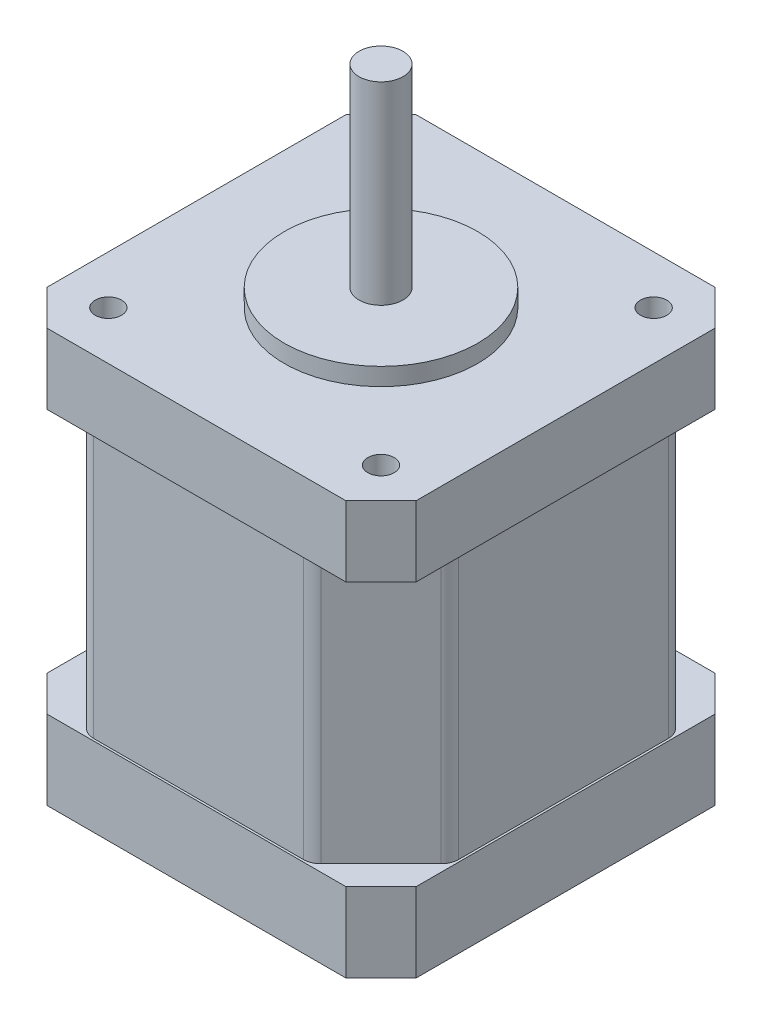
SolidWorks part; units mm, degrees
material "Commercially Pure CP-Ti UNS R50700  Grade 4 (SS)"
ref_plane "Front Plane" through (0, 0, 0) normal (0, 0, 1) x (1, 0, 0)
ref_plane "Top Plane" through (0, 0, 0) normal (0, 1, 0) x (1, 0, 0)
ref_plane "Right Plane" through (0, 0, 0) normal (1, 0, 0) x (0, 0, -1)
sketch "Sketch1" plane through (0, 0, 0) normal (0, 1, 0) x (1, 0, 0)
  line L0 (-21, 21) -> (21, -21) construction
  line L1 (-17, 21) -> (17, 21)
  line L2 (-21, 17) -> (-21, -17)
  line L3 (-17, -21) -> (17, -21)
  line L4 (21, 17) -> (21, -17)
  line L5 (-21, 17) -> (-17, 21)
  line L6 (-21, -17) -> (-17, -21)
  line L7 (17, -21) -> (21, -17)
  line L8 (17, 21) -> (21, 17)
  line L9 (-15.5, 15.5) -> (15.5, 15.5) construction
  line L10 (15.5, 15.5) -> (15.5, -15.5) construction
  line L11 (15.5, -15.5) -> (-15.5, -15.5) construction
  line L12 (-15.5, -15.5) -> (-15.5, 15.5) construction
  line L13 (15.5, 15.5) -> (-15.5, -15.5) construction
  circle A0 centre (-15.5, 15.5) radius 1.5
  circle A1 centre (-15.5, -15.5) radius 1.5
  circle A2 centre (15.5, -15.5) radius 1.5
  circle A3 centre (15.5, 15.5) radius 1.5
  point P2 (-21, -21)
  point P3 (21, 21)
  dimension "D2" = 3
  dimension "D3" = 31
  dimension "D1" = 42
extrude "Boss-Extrude1" add sketch "Sketch1" along normal blind 8
sketch "Sketch2" plane through (0, 0, 0) normal (0, -1, 0) x (1, 0, 0)
  line L1 (-12.75, 20.75) -> (12.75, 20.75)
  line L2 (-20.75, 12.75) -> (-20.75, -12.75)
  line L3 (-12.75, -20.75) -> (12.75, -20.75)
  line L4 (20.75, 12.75) -> (20.75, -12.75)
  line L9 (12.75, 20.75) -> (20.75, 12.75)
  line L10 (12.75, -20.75) -> (20.75, -12.75)
  line L11 (-20.75, -12.75) -> (-12.75, -20.75)
  line L12 (-20.75, 12.75) -> (-12.75, 20.75)
  line L13 (0, -20.75) -> (0, 0) construction
  line L14 (0, 0) -> (-20.75, 0) construction
  point P0 (-20.75, 20.75)
  point P1 (20.75, -20.75)
  point P2 (-20.75, -20.75)
  point P3 (20.75, 20.75)
  dimension "D2" = 41.5
extrude "Boss-Extrude2" add sketch "Sketch2" along normal blind 30
fillet "Fillet1" radius 2 8 edges at (12.75, -15, 20.75) (20.75, -15, 12.75) (20.75, -15, -12.75) (12.75, -15, -20.75) (-12.75, -15, -20.75) (-20.75, -15, -12.75) (-20.75, -15, 12.75) (-12.75, -15, 20.75)
sketch "Sketch3" plane through (0, -30, 0) normal (0, -1, 0) x (1, 0, 0)
  line L0 (-21, 17) -> (-21, -17)
  line L1 (-21, -17) -> (-17, -21)
  line L2 (-17, -21) -> (17, -21)
  line L3 (17, -21) -> (21, -17)
  line L4 (21, -17) -> (21, 17)
  line L5 (21, 17) -> (17, 21)
  line L6 (17, 21) -> (-17, 21)
  line L7 (-17, 21) -> (-21, 17)
extrude "Boss-Extrude3" add sketch "Sketch3" along normal blind 9
sketch "Sketch4" plane through (0, 8, 0) normal (0, 1, 0) x (1, 0, 0)
  circle A0 centre (0, 0) radius 11
  dimension "D1" = 22
extrude "Boss-Extrude4" add sketch "Sketch4" along normal blind 2
sketch "Sketch5" plane through (0, 10, 0) normal (0, 1, 0) x (1, 0, 0)
  circle A0 centre (0, 0) radius 2.5
  dimension "D1" = 5
extrude "Boss-Extrude5" add sketch "Sketch5" along normal blind 22
